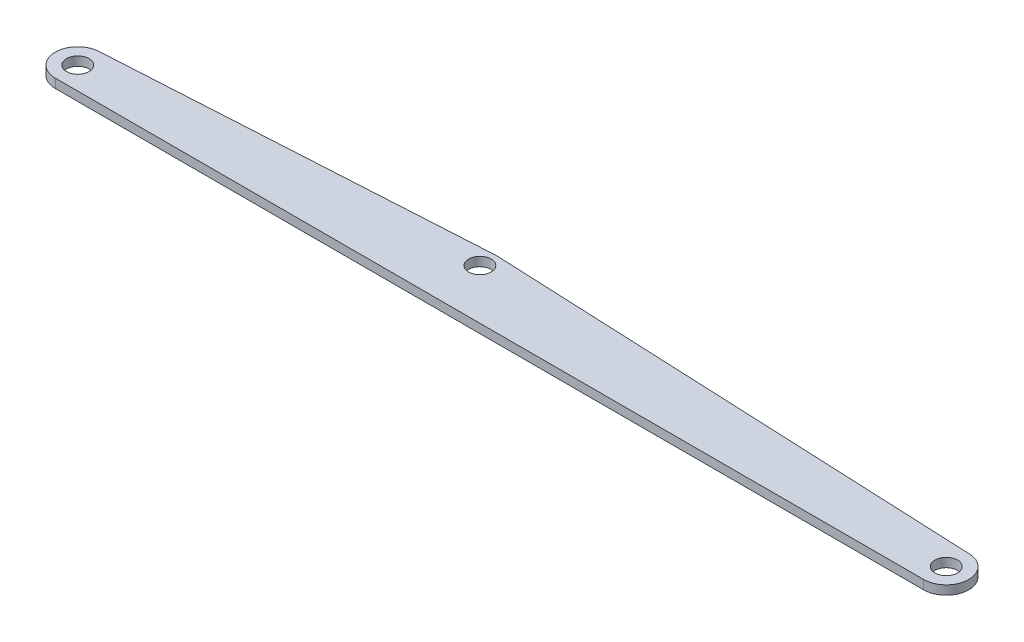
SolidWorks part; units mm, degrees
ref_plane "Front Plane" through (0, 0, 0) normal (0, 0, 1) x (1, 0, 0)
ref_plane "Top Plane" through (0, 0, 0) normal (0, 1, 0) x (1, 0, 0)
ref_plane "Right Plane" through (0, 0, 0) normal (1, 0, 0) x (0, 0, -1)
sketch "Sketch2" plane through (0, 0, 0) normal (0, 1, 0) x (1, 0, 0)
  line L0 (0, 0) -> (0, 12.7) construction
  line L1 (0, 0) -> (12.7, 0) construction
  line L2 (0, 0) -> (0, -12.7) construction
  line L3 (0, 0) -> (-279, 0) construction
  line L4 (0, 0) -> (-489.9, 0) construction
  line L5 (-489.9, 0) -> (-489.9, 12.7) construction
  line L6 (-489.9, 0) -> (-489.9, -12.7) construction
  line L7 (-489.9, 0) -> (-502.6, 0) construction
  line L8 (-489.9, -12.7) -> (0, -12.7)
  line L10 (-489.9, 0) -> (-278.5685, 15.5113) construction
  line L11 (-489.9, 12.7) -> (-279.1243, 25.0201)
  line L12 (0, 12.7) -> (-278.1468, 25.0269)
  circle A0 centre (0, 0) radius 6.35
  arc A1 (0, 12.7) -> (0, -12.7) centre (0, 0) cw
  circle A3 centre (-489.9, 0) radius 6.35
  arc A4 (-489.9, 12.7) -> (-489.9, -12.7) centre (-489.9, 0) ccw
  circle A5 centre (-278.5685, 15.5113) radius 6.35
  arc A6 (-278.1468, 25.0269) -> (-279.1243, 25.0201) centre (-278.5685, 15.5113) ccw
  dimension "D1" = 12.7
  dimension "D6" = 211.9
  dimension "D8" = 12.7
  dimension "D11" = 12.7
  dimension "D12" = 19.05
  dimension "D2" = 12.7
  dimension "D3" = 12.7
  dimension "D4" = 12.7
  dimension "D5" = 279
  dimension "D7" = 489.9
  dimension "D9" = 12.7
  dimension "D10" = 4.198
extrude "Boss-Extrude1" add sketch "Sketch2" along normal blind 5.08
ref_point "Point1"
